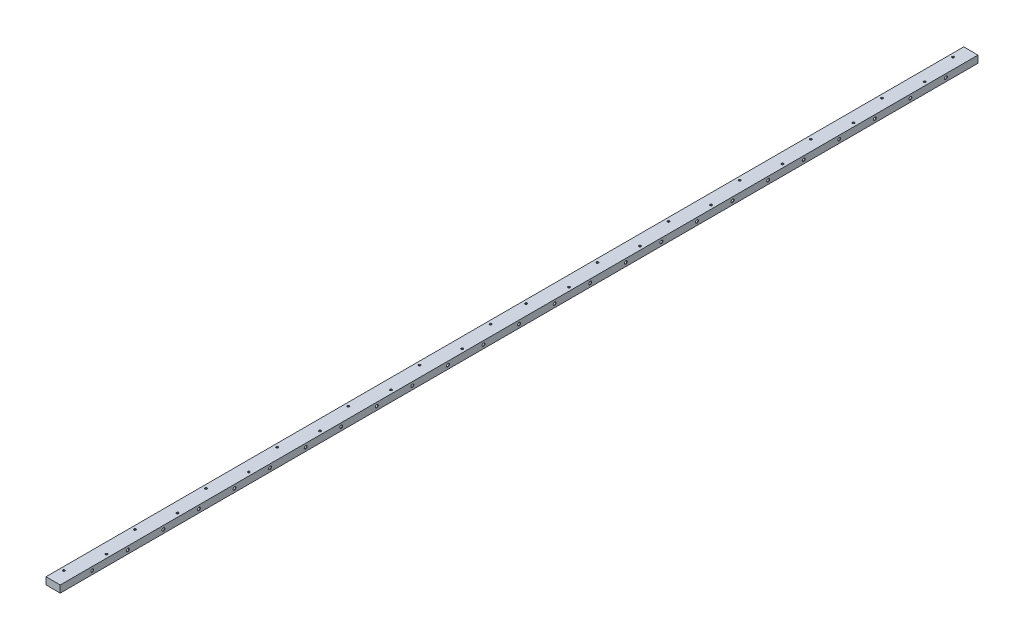
SolidWorks part; units mm, degrees
material "Plain Carbon Steel"
ref_plane "Front Plane" through (0, 0, 0) normal (0, 0, 1) x (1, 0, 0)
ref_plane "Top Plane" through (0, 0, 0) normal (0, 1, 0) x (1, 0, 0)
ref_plane "Right Plane" through (0, 0, 0) normal (1, 0, 0) x (0, 0, -1)
sketch "Sketch1" plane through (0, 0, 0) normal (0, 0, 1) x (1, 0, 0)
  line L1 (-10, -5) -> (10, -5)
  line L2 (-10, -5) -> (-10, 5)
  line L3 (-10, 5) -> (10, 5)
  line L4 (10, -5) -> (10, 5)
  line L5 (-10, -5) -> (10, 5) construction
  line L6 (-10, 5) -> (10, -5) construction
  point P0 (0, 0)
  dimension "D1" = 10
  dimension "D2" = 20
extrude "Boss-Extrude1" add sketch "Sketch1" along normal mid plane 1290
sketch "Sketch4" plane through (0, 5, 0) normal (0, 1, 0) x (1, 0, 0)
  line L0 (0, -75) -> (-5, -75) construction
  line L1 (-5, -75) -> (-5, 0) construction
  line L2 (-5, 0) -> (5, 0) construction
  line L3 (5, 0) -> (5, -75) construction
  line L4 (5, -75) -> (0, -75) construction
  line L6 (5, -25) -> (-5, -25) construction
  circle A0 centre (-5, -25) radius 1.25
  circle A1 centre (5, -75) radius 1.25
  point P5 (0, 0)
  dimension "D3" = 2.5
  dimension "D1" = 50
  dimension "D2" = 10
  dimension "D4" = 25
hole_wizard "M3x0.5 Tapped Hole1" positions "Sketch6" profile "Sketch7" tap size "M3x0.5" standard "ANSI Metric"
sketch "Sketch6" plane through (0, 5, 0) normal (0, 1, 0) x (1, 0, 0)
  point P0 (-5, -25)
  point P3 (5, -75)
sketch "Sketch7" plane through (-5, 5, 25) normal (1, 0, 0) x (0, 0, 1)
  line L0 (0, 0) -> (0, 8.7511)
  line L1 (0, 8.7511) -> (1.25, 8)
  line L2 (1.25, 8) -> (1.25, 0.6639)
  line L3 (1.25, 0.6639) -> (1.525, 0)
  line L5 (1.525, 0) -> (0, 0)
  line L6 (-1.25, 0.6639) -> (-1.525, 0) construction
  line L10 (0, 8.7511) -> (-1.25, 8) construction
  line L11 (0, -6.35) -> (0, 107.95) construction
  dimension "Tap Drill Dia." = 2.5
  dimension "Tap Drill Depth" = 8
  dimension "Near C'Sink Dia." = 3.05
  dimension "Near C'Sink Angle" = 45
  dimension "Drill Angle" = 118
cosmetic thread "Hole Thread3" parameters "D1"=6, "D2"=3
cosmetic thread "Hole Thread4" parameters "D1"=6, "D2"=3
pattern_linear "LPattern1" count 7 spacing 100 along (0, 0, 1) of "M3x0.5 Tapped Hole1"
mirror "Mirror1" about plane through (0, 0, 0) normal (0, 0, 1) of "LPattern1", "M3x0.5 Tapped Hole1"
hole_wizard "M4x0.7 Tapped Hole1" positions "Sketch8" profile "Sketch9" tap size "M4x0.7" standard "ANSI Metric" end condition through all
sketch "Sketch8" plane through (-10, 0, 0) normal (-1, 0, 0) x (0, 0, 1)
  point P0 (0, 0)
sketch "Sketch9" plane through (-10, 0, 0) normal (0, 1, 0) x (0, 0, 1)
  line L0 (0, 0) -> (0, 20)
  line L1 (0, 20) -> (2.05, 20)
  line L2 (1.65, 19.6) -> (1.65, 0.4)
  line L3 (1.65, 0.4) -> (2.05, 0)
  line L5 (2.05, 0) -> (0, 0)
  line L6 (-1.65, 0.4) -> (-2.05, 0) construction
  line L7 (2.05, 20) -> (1.65, 19.6)
  line L8 (-2.05, 20) -> (-1.65, 19.6) construction
  line L11 (0, -6.35) -> (0, 107.95) construction
  dimension "Thru Tap Drill Dia." = 3.3
  dimension "Thru Tap Drill Depth" = 20
  dimension "Near C'Sink Dia." = 4.1
  dimension "Near C'Sink Angle" = 90
  dimension "Far C'Sink Dia." = 4.1
  dimension "Far C'Sink Angle" = 90
cosmetic thread "Hole Thread5" parameters "D2"=4
pattern_linear "LPattern2" count 13 spacing 50 along (0, 0, 1) count 13 spacing 50 along (0, 0, -1) of "M4x0.7 Tapped Hole1"
